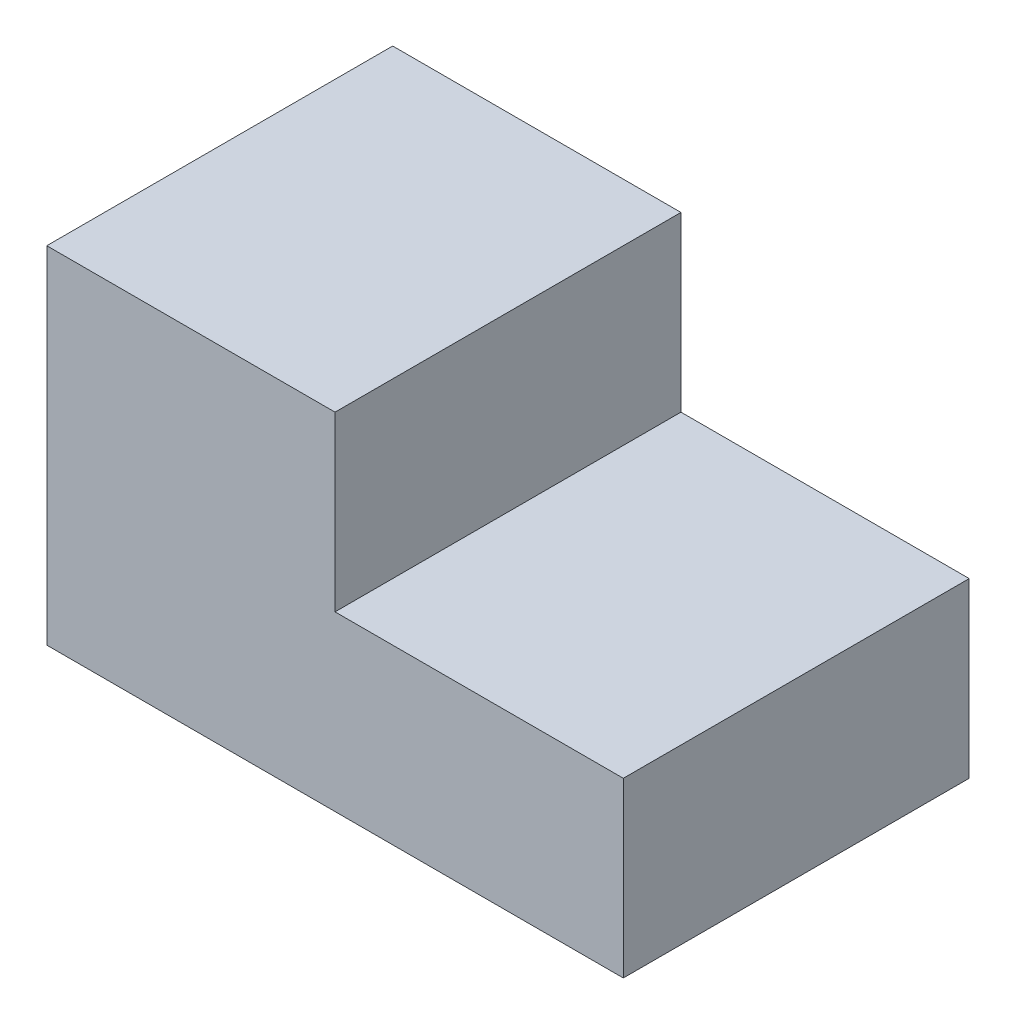
SolidWorks part; units mm, degrees
ref_plane "Plano frontal" through (0, 0, 0) normal (0, 0, 1) x (1, 0, 0)
ref_plane "Plano superior" through (0, 0, 0) normal (0, 1, 0) x (1, 0, 0)
ref_plane "Plano direito" through (0, 0, 0) normal (1, 0, 0) x (0, 0, -1)
sketch "Esboço2" plane through (0, 0, 0) normal (0, 0, 1) x (1, 0, 0)
  line L0 (0, 0) -> (-100, 0)
  line L1 (-100, 0) -> (-100, 60)
  line L2 (-100, 60) -> (-50, 60)
  line L3 (-50, 60) -> (-50, 30)
  line L4 (-50, 30) -> (0, 30)
  line L5 (0, 30) -> (0, 0)
  dimension "D1" = 100
  dimension "D2" = 60
  dimension "D3" = 50
  dimension "D4" = 30
extrude "Ressalto-extrusão1" add sketch "Esboço2" along normal blind 60 contours L0 L1 L2 L3 L4 L5
